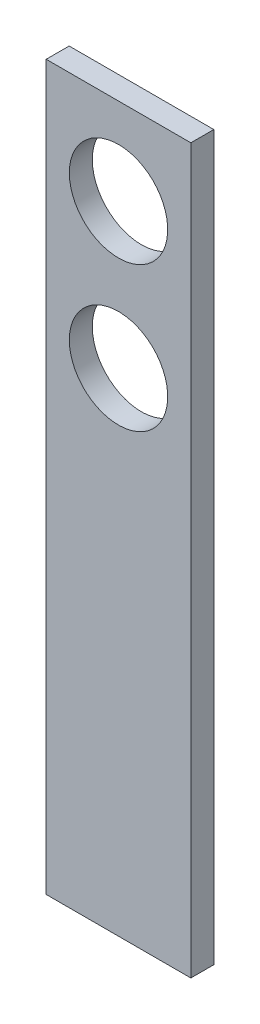
SolidWorks part; units mm, degrees
ref_plane "Front Plane" through (0, 0, 0) normal (0, 0, 1) x (1, 0, 0)
ref_plane "Top Plane" through (0, 0, 0) normal (0, 1, 0) x (1, 0, 0)
ref_plane "Right Plane" through (0, 0, 0) normal (1, 0, 0) x (0, 0, -1)
sketch "Sketch1" plane through (0, 0, 0) normal (0, 0, 1) x (1, 0, 0)
  line L1 (-1.9093, 4.5467) -> (3.0907, 4.5467)
  line L2 (-1.9093, 4.5467) -> (-1.9093, -20.4533)
  line L3 (-1.9093, -20.4533) -> (3.0907, -20.4533)
  line L4 (3.0907, 4.5467) -> (3.0907, -20.4533)
  dimension "D1" = 5
  dimension "D2" = 25
extrude "Boss-Extrude1" add sketch "Sketch1" along normal blind 0.7937
sketch "Sketch2" plane through (0, 0, 0) normal (0, 0, -1) x (-1, 0, 0)
  line L0 (-3.0907, 4.5467) -> (1.9093, 4.5467) construction
  circle A0 centre (-0.5907, 1.5467) radius 0.6057
  circle A1 centre (-0.5907, -3.4533) radius 0.9424
  dimension "D1" = 3
  dimension "D2" = 5
hole_wizard "M3 Clearance Hole1" positions "Sketch3" profile "Sketch4" hole size "M3" standard "ANSI Metric" end condition through all
sketch "Sketch3" plane through (0, 0, 0) normal (0, 0, -1) x (-1, 0, 0)
  point P0 (-0.5907, 1.5467)
  point P3 (-0.5907, -3.4533)
sketch "Sketch4" plane through (0.5907, 1.5467, 0) normal (1, 0, 0) x (0, 1, 0)
  line L0 (0, 0) -> (0, 0.7937)
  line L1 (0, 0.7937) -> (1.7, 0.7937)
  line L2 (1.7, 0.7937) -> (1.7, 0)
  line L5 (1.7, 0) -> (0, 0)
  line L11 (0, -6.35) -> (0, 107.95) construction
  dimension "Thru Hole Dia." = 3.4
  dimension "Thru Hole Depth" = 0.7937
